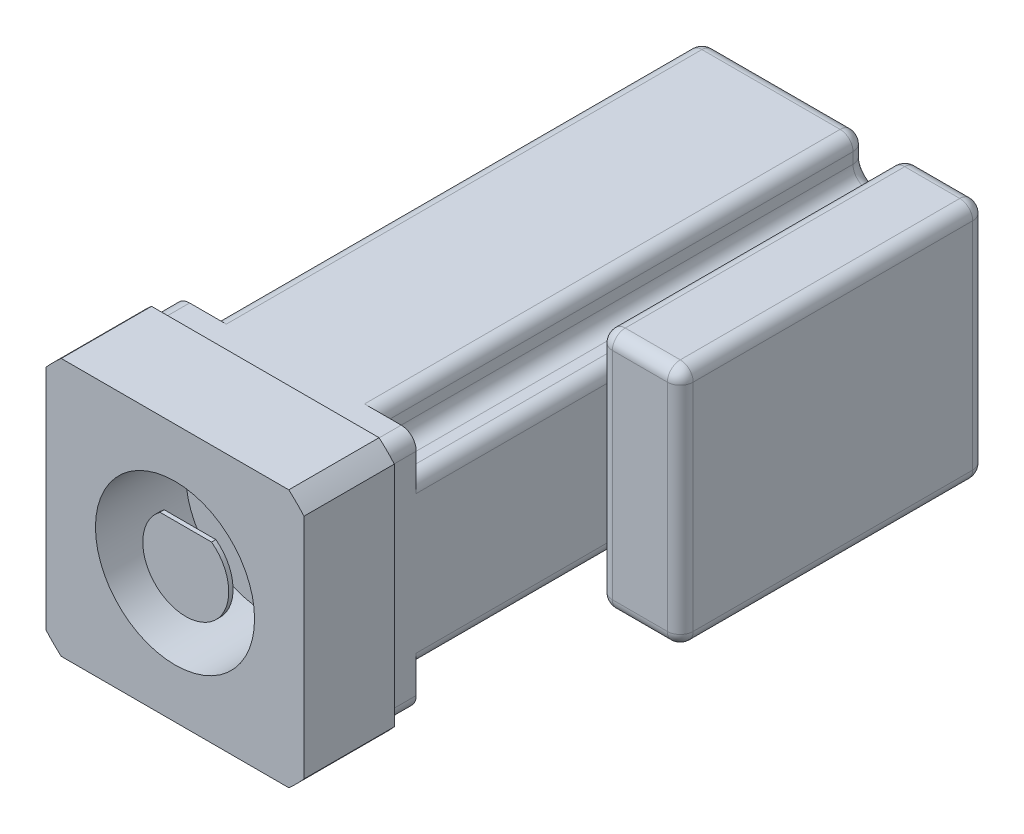
SolidWorks part; units mm, degrees
ref_plane "Front Plane" through (0, 0, 0) normal (0, 0, 1) x (1, 0, 0)
ref_plane "Top Plane" through (0, 0, 0) normal (0, 1, 0) x (1, 0, 0)
ref_plane "Right Plane" through (0, 0, 0) normal (1, 0, 0) x (0, 0, -1)
sketch "Sketch1" plane through (0, 0, 0) normal (0, 0, 1) x (1, 0, 0)
  line L0 (-6, 8) -> (6, 8)
  line L1 (0, 8) -> (0, 0) construction
  line L2 (0, 0) -> (-10, 0) construction
  line L3 (0, 0) -> (-7.0711, 7.0711) construction
  arc A0 (-6, 8) -> (6, 8) centre (0, 0) ccw
  dimension "D4" = 10
  dimension "D1" = 45
  dimension "D2" = 45
  dimension "D3" = 8
extrude "Boss-Extrude1" add sketch "Sketch1" along normal blind 1
sketch "Sketch2" plane through (0, 0, 0) normal (0, 0, 1) x (1, 0, 0)
  line L1 (-26.4575, 30) -> (26.4575, 30)
  line L2 (-30, 26.4575) -> (-30, -26.4575)
  line L3 (-26.4575, -30) -> (26.4575, -30)
  line L4 (30, 26.4575) -> (30, -26.4575)
  line L5 (0, -30) -> (0, 30) construction
  line L6 (-30, 0) -> (30, 0) construction
  arc A0 (-26.4575, 30) -> (-30, 26.4575) centre (0, 0) ccw
  arc A1 (30, 26.4575) -> (26.4575, 30) centre (0, 0) ccw
  arc A2 (26.4575, -30) -> (30, -26.4575) centre (0, 0) ccw
  arc A3 (-30, -26.4575) -> (-26.4575, -30) centre (0, 0) ccw
  circle A4 centre (0, 0) radius 18.5
  point P0 (0, 0)
  dimension "D2" = 80
  dimension "D3" = 37
  dimension "D1" = 60
extrude "Boss-Extrude2" add sketch "Sketch2" against normal blind 21 from offset 3.5 separate body
sketch "Sketch3" plane through (0, 0, -17.5) normal (0, 0, -1) x (-1, 0, 0)
  line L1 (28.1, 28.1) -> (-28.1, 28.1)
  line L2 (28.1, 28.1) -> (28.1, -28.1)
  line L3 (28.1, -28.1) -> (-28.1, -28.1)
  line L4 (-28.1, 28.1) -> (-28.1, -28.1)
  line L5 (0, -28.1) -> (0, 28.1) construction
  line L6 (28.1, 0) -> (-28.1, 0) construction
  point P0 (0, 0)
  dimension "D1" = 56.2
extrude "Boss-Extrude3" add sketch "Sketch3" along normal blind 120.6 separate body
sketch "Sketch4" plane through (0, 0, -138.1) normal (0, 0, -1) x (-1, 0, 0)
  line L1 (-28.1, 28.1) -> (-19.07, 28.1)
  line L2 (-28.1, 28.1) -> (-28.1, 19.07)
  line L3 (-28.1, 19.07) -> (-19.07, 19.07)
  line L4 (-19.07, 28.1) -> (-19.07, 19.07)
  line L5 (28.1, 28.1) -> (19.07, 28.1)
  line L6 (28.1, 28.1) -> (28.1, 19.07)
  line L7 (28.1, 19.07) -> (19.07, 19.07)
  line L8 (19.07, 28.1) -> (19.07, 19.07)
  line L9 (28.1, -28.1) -> (19.07, -28.1)
  line L10 (28.1, -28.1) -> (28.1, -19.07)
  line L11 (28.1, -19.07) -> (19.07, -19.07)
  line L12 (19.07, -28.1) -> (19.07, -19.07)
  line L13 (-28.1, -28.1) -> (-19.07, -28.1)
  line L14 (-28.1, -28.1) -> (-28.1, -19.07)
  line L15 (-28.1, -19.07) -> (-19.07, -19.07)
  line L16 (-19.07, -28.1) -> (-19.07, -19.07)
  circle A0 centre (0, 0) radius 26.9691 construction
  dimension "D1" = 9.03
extrude "Cut-Extrude1" cut sketch "Sketch4" against normal offset from surface (113.6 mm away) 7 up to face at (0, 0, -17.5)
fillet "Fillet1" radius 3.5 8 edges at (-28.1, -28.1, -21) (28.1, -28.1, -21) (-28.1, 28.1, -21) (28.1, 28.1, -21) (-19.07, 19.07, -81.3) (-19.07, -19.07, -81.3) (19.07, -19.07, -81.3) (19.07, 19.07, -81.3)
fillet "Fillet2" radius 3 8 edges at (19.07, -28.1, -81.3) (28.1, -19.07, -81.3) (28.1, 19.07, -81.3) (19.07, 28.1, -81.3) (-19.07, 28.1, -81.3) (-28.1, 19.07, -81.3) (-28.1, -19.07, -81.3) (-19.07, -28.1, -81.3)
fillet "Fillet3" radius 3 24 edges at (27.2213, 18.1913, -138.1) (23.835, 19.07, -138.1) (20.0951, 20.0951, -138.1) (19.07, 23.835, -138.1) (18.1913, 27.2213, -138.1) (0, 28.1, -138.1) (-18.1913, 27.2213, -138.1) (-19.07, 23.835, -138.1) (-20.0951, 20.0951, -138.1) (-23.835, 19.07, -138.1) (-27.2213, 18.1913, -138.1) (-28.1, 0, -138.1) (-27.2213, -18.1913, -138.1) (-23.835, -19.07, -138.1) (-20.0951, -20.0951, -138.1) (-19.07, -23.835, -138.1) (-18.1913, -27.2213, -138.1) (0, -28.1, -138.1) (18.1913, -27.2213, -138.1) (19.07, -23.835, -138.1) (20.0951, -20.0951, -138.1) (23.835, -19.07, -138.1) (27.2213, -18.1913, -138.1) (28.1, 0, -138.1)
sketch "Sketch5" plane through (28.1, 0, 0) normal (1, 0, 0) x (0, 0, -1)
  line L0 (138.1, 16.07) -> (138.1, -16.07) construction
  line L1 (138.1, 28.1) -> (67.1, 28.1)
  line L2 (138.1, 28.1) -> (138.1, -28.1)
  line L3 (138.1, -28.1) -> (67.1, -28.1)
  line L4 (67.1, 28.1) -> (67.1, -28.1)
  line L5 (102.6, -28.1) -> (102.6, 28.1) construction
  line L6 (138.1, 0) -> (67.1, 0) construction
  line L8 (17.5, -26.4575) -> (17.5, 26.4575) construction
  point P0 (102.6, 0)
  dimension "D1" = 49.6
  dimension "D2" = 56.2
extrude "Boss-Extrude4" add sketch "Sketch5" along normal blind 18.8
fillet "Fillet5" radius 3 8 edges at (46.9, 28.1, -102.6) (37.5, 28.1, -67.1) (28.1, 28.1, -102.6) (28.1, 0, -67.1) (28.1, -28.1, -102.6) (37.5, -28.1, -67.1) (46.9, 0, -67.1) (46.9, -28.1, -102.6)
fillet "Fillet7" radius 3 8 edges at (46.0213, -27.2213, -138.1) (37.5, -28.1, -138.1) (28.9787, -27.2213, -138.1) (28.1, 0, -138.1) (28.9787, 27.2213, -138.1) (37.5, 28.1, -138.1) (46.0213, 27.2213, -138.1) (46.9, 0, -138.1)
